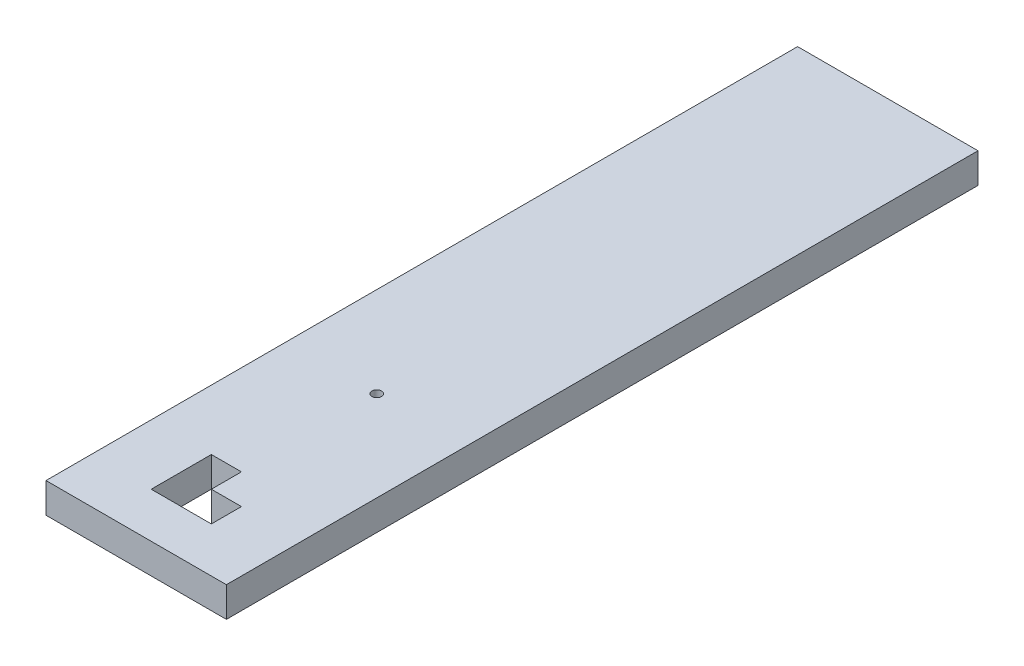
SolidWorks part; units mm, degrees
ref_plane "Front Plane" through (0, 0, 0) normal (0, 0, 1) x (1, 0, 0)
ref_plane "Top Plane" through (0, 0, 0) normal (0, 1, 0) x (1, 0, 0)
ref_plane "Right Plane" through (0, 0, 0) normal (1, 0, 0) x (0, 0, -1)
sketch "Sketch1" plane through (0, 0, 0) normal (0, 1, 0) x (1, 0, 0)
  line L0 (30, 0) -> (30, -250) construction
  line L1 (0, 0) -> (60, 0)
  line L2 (0, 0) -> (0, -250)
  line L3 (0, -250) -> (60, -250)
  line L4 (60, 0) -> (60, -250)
  line L6 (20, -215) -> (20, -235)
  line L7 (20, -235) -> (40, -235)
  line L9 (20, -215) -> (30, -215)
  line L10 (30, -215) -> (30, -225)
  line L11 (30, -225) -> (40, -225)
  line L12 (40, -225) -> (40, -235)
  circle A0 centre (30, -170) radius 1.6
  dimension "D3" = 3.2
  dimension "D1" = 60
  dimension "D2" = 250
  dimension "D4" = 30
  dimension "D5" = 80
  dimension "D6" = 20
  dimension "D7" = 20
  dimension "D8" = 20
  dimension "D9" = 10
  dimension "D10" = 10
extrude "Boss-Extrude1" add sketch "Sketch1" along normal blind 10
